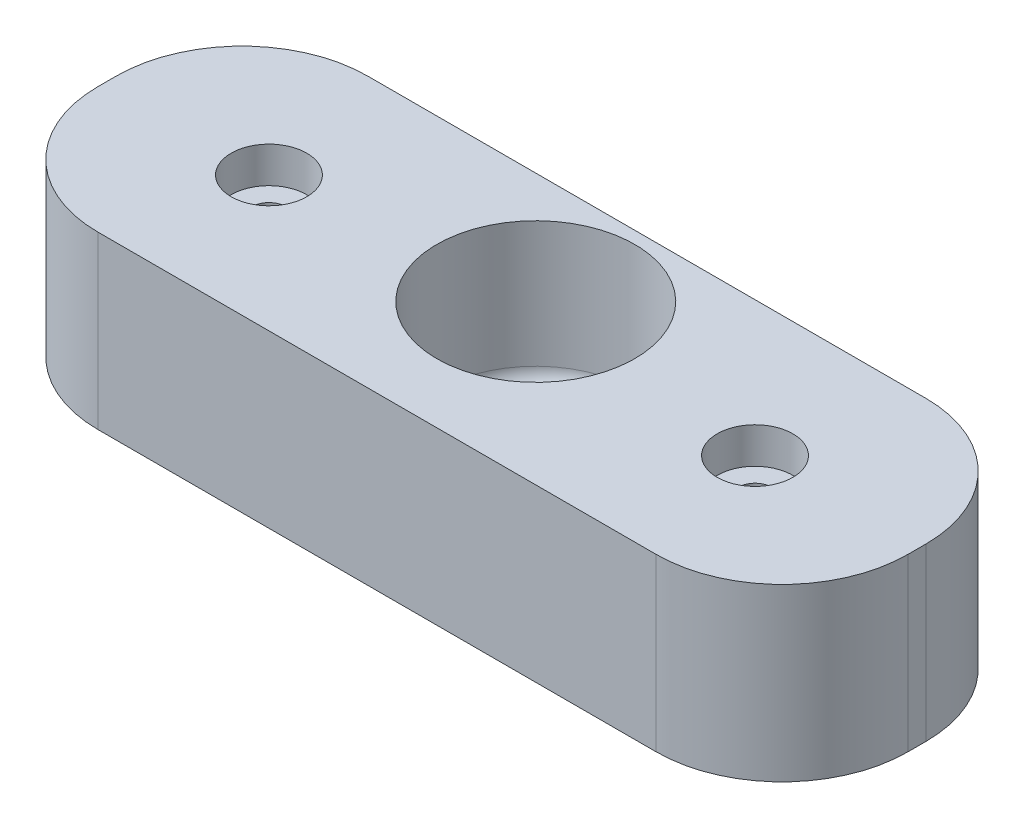
SolidWorks part; units mm, degrees
ref_plane "Front Plane" through (0, 0, 0) normal (0, 0, 1) x (1, 0, 0)
ref_plane "Top Plane" through (0, 0, 0) normal (0, 1, 0) x (1, 0, 0)
ref_plane "Right Plane" through (0, 0, 0) normal (1, 0, 0) x (0, 0, -1)
sketch "Sketch1" plane through (0, 0, 0) normal (0, 1, 0) x (1, 0, 0)
  line L1 (0, 0) -> (45, 0)
  line L2 (0, 0) -> (0, 15)
  line L3 (0, 15) -> (45, 15)
  line L4 (45, 0) -> (45, 15)
  dimension "D1" = 45
  dimension "D2" = 15
extrude "Boss-Extrude1" add sketch "Sketch1" against normal blind 9.5
sketch "Sketch2" plane through (0, 0, 0) normal (0, 1, 0) x (1, 0, 0)
  line L0 (45, 15) -> (0, 15) construction
  line L1 (0, 15) -> (0, 0) construction
  circle A0 centre (22.5, 8.82) radius 5.5
  dimension "D2" = 11
  dimension "D1" = 6.18
  dimension "D3" = 22.5
extrude "Cut-Extrude1" cut sketch "Sketch2" against normal blind 8
sketch "Sketch3" plane through (0, -8, 0) normal (0, 1, 0) x (1, 0, 0)
  circle A0 centre (22.5, 8.82) radius 2.2
  dimension "D1" = 4.4
extrude "Cut-Extrude2" cut sketch "Sketch3" against normal up to next
sketch "Sketch4" plane through (0, 0, 0) normal (0, 1, 0) x (1, 0, 0)
  line L0 (45, 15) -> (0, 15) construction
  circle A0 centre (9, 7.5) radius 2.1
  circle A1 centre (36, 7.5) radius 2.1
  circle A3 centre (22.5, 8.82) radius 5.5 construction
  dimension "D3" = 4.2
  dimension "D4" = 13.5
  dimension "D5" = 13.5
  dimension "D1" = 7.5
  dimension "D2" = 7.5
extrude "Cut-Extrude3" cut sketch "Sketch4" against normal blind 2
fillet "Fillet1" radius 7 4 edges at (45, -4.75, -15) (0, -4.75, -15) (45, -4.75, 0) (0, -4.75, 0)
sketch "Sketch5" plane through (0, -9.5, 0) normal (0, -1, 0) x (-1, 0, 0)
  line L0 (-38, 15) -> (-7, 15) construction
  circle A0 centre (-36, 7.5) radius 2.05
  circle A1 centre (-9, 7.5) radius 2.05
  circle A2 centre (-22.5, 8.82) radius 2.2 construction
  dimension "D5" = 4.1
  dimension "D1" = 7.5
  dimension "D2" = 7.5
  dimension "D3" = 13.5
  dimension "D4" = 13.5
extrude "Cut-Extrude4" cut sketch "Sketch5" against normal blind 5
sketch "Sketch6" plane through (0, -2, 0) normal (0, 1, 0) x (1, 0, 0)
  circle A1 centre (9, 7.5) radius 0.95
  circle A2 centre (36, 7.5) radius 0.95
  dimension "D1" = 1.9
extrude "Cut-Extrude5" cut sketch "Sketch6" against normal blind 3
fillet "Fillet5" radius 1 2 edges at (22.5, -8, -3.32) (22.5, -8, -6.62)
